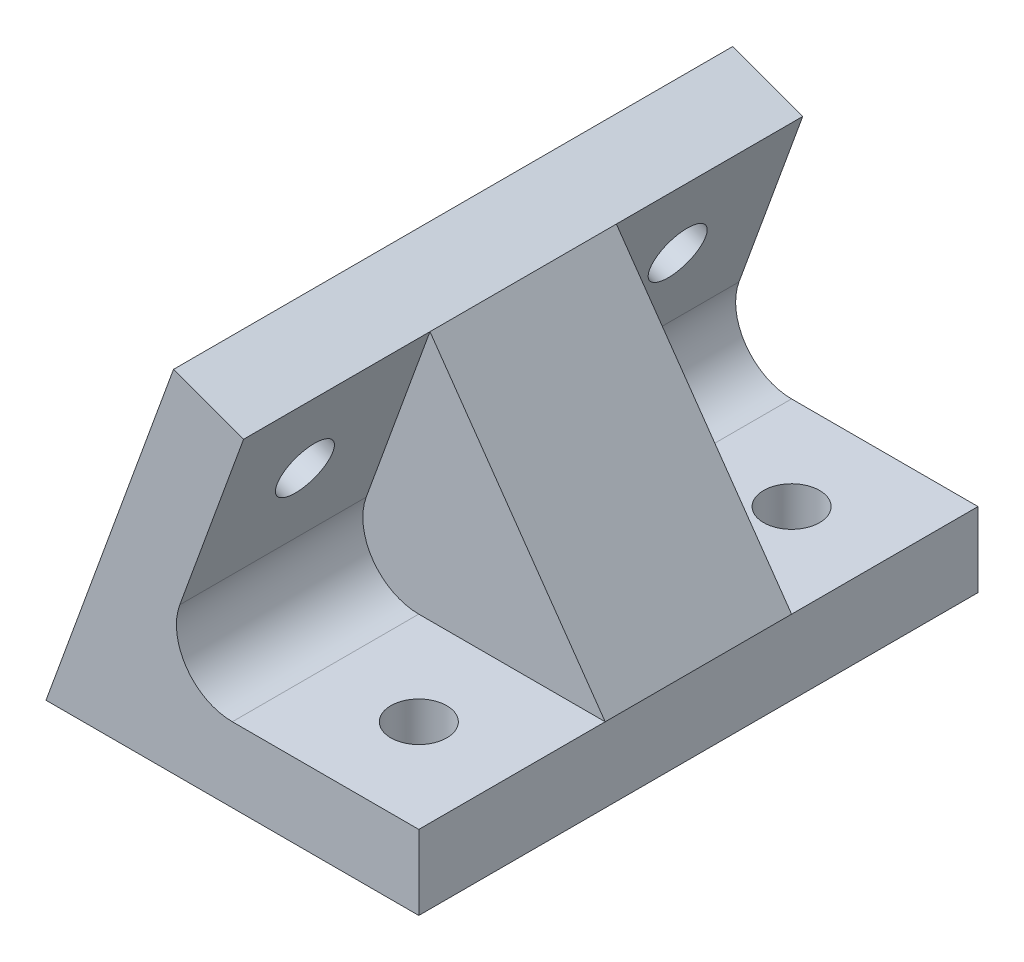
SolidWorks part; units mm, degrees
material "ABS"
ref_plane "前视基准面" through (0, 0, 0) normal (0, 0, 1) x (1, 0, 0)
ref_plane "上视基准面" through (0, 0, 0) normal (0, 1, 0) x (1, 0, 0)
ref_plane "右视基准面" through (0, 0, 0) normal (1, 0, 0) x (0, 0, -1)
sketch "草图1" plane through (0, 0, 0) normal (0, 0, 1) x (1, 0, 0)
  line L0 (0, 0) -> (20, 0)
  line L1 (20, 0) -> (20, 4)
  line L2 (20, 4) -> (5.7126, 4)
  line L3 (5.7126, 4) -> (10.5992, 17.4258)
  line L4 (10.5992, 17.4258) -> (6.8404, 18.7939)
  line L5 (6.8404, 18.7939) -> (0, 0)
  dimension "D1" = 70
  dimension "D2" = 20
  dimension "D3" = 4
  dimension "D4" = 20
extrude "凸台-拉伸1" add sketch "草图1" along normal blind 30
sketch "草图2" plane through (0, 0, 0) normal (0, -1, 0) x (1, 0, 0)
  line L0 (15, 30) -> (15, 0) construction
  line L1 (0, 30) -> (20, 30) construction
  line L2 (0, 0) -> (20, 0) construction
  line L3 (0, 30) -> (0, 0) construction
  line L4 (15, 15) -> (20, 15) construction
  line L5 (20, 30) -> (20, 0) construction
  circle A0 centre (15, 25) radius 1.5
  circle A1 centre (15, 5) radius 1.5
  dimension "D2" = 3
  dimension "D1" = 15
  dimension "D3" = 10
extrude "切除-拉伸1" cut sketch "草图2" against normal blind 5
ref_plane "基准面1" through (0, 0, 0) normal (-0.5736, 0.8192, 0) x (0.8192, 0.5736, 0)
mirror "镜向1" about plane through (0, 0, 0) normal (-0.5736, 0.8192, 0) of "切除-拉伸1"
ref_plane "基准面2" through (0, 0, 15) normal (0, 0, 1) x (1, 0, 0)
sketch "草图3" plane through (0, 0, 15) normal (0, 0, 1) x (1, 0, 0)
  line L5 (20, 4) -> (5.7126, 4) construction
  line L6 (5.7126, 4) -> (10.5992, 17.4258) construction
  line L7 (20, 4) -> (5.7126, 4) construction
  line L8 (5.7126, 4) -> (10.5992, 17.4258) construction
  line L10 (10.5992, 17.4258) -> (20, 4)
rib "筋11" sketch "草图3" sketch "草图3" thickness 10 extrusion direction parallel to sketch draft on no parameters "D1"=10
fillet "圆角1" radius 3 2 edges at (5.7126, 4, 5) (5.7126, 4, 25)
